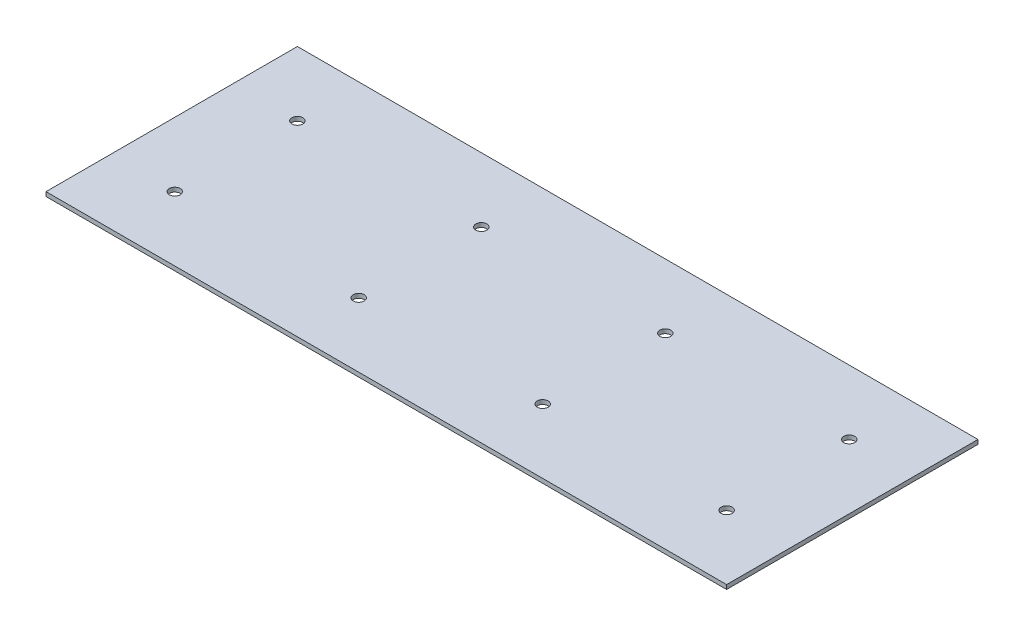
SolidWorks part; units mm, degrees
ref_plane "Front Plane" through (0, 0, 0) normal (0, 0, 1) x (1, 0, 0)
ref_plane "Top Plane" through (0, 0, 0) normal (0, 1, 0) x (1, 0, 0)
ref_plane "Right Plane" through (0, 0, 0) normal (1, 0, 0) x (0, 0, -1)
sketch "Sketch1" plane through (0, 0, 0) normal (0, 1, 0) x (1, 0, 0)
  line L1 (0, 0) -> (255.3, 0)
  line L2 (0, 0) -> (0, 94.3)
  line L3 (0, 94.3) -> (255.3, 94.3)
  line L4 (255.3, 0) -> (255.3, 94.3)
  dimension "D1" = 255.3
  dimension "D2" = 94.3
extrude "Boss-Extrude1" add sketch "Sketch1" along normal blind 1.6
ref_plane "Plane1" through (0, 0, -47.15) normal (0, 0, 1) x (1, 0, 0)
ref_plane "Plane2" through (127.65, 0, 0) normal (1, 0, 0) x (0, 0, -1)
sketch "Sketch3" plane through (0, 1.6, 0) normal (0, 1, 0) x (1, 0, 0)
  circle A0 centre (24.15, 70.15) radius 2.05
  circle A1 centre (24.15, 24.15) radius 2.05
  circle A3 centre (93.15, 70.15) radius 2.05
  circle A4 centre (93.15, 24.15) radius 2.05
  circle A5 centre (162.15, 24.15) radius 2.05
  circle A6 centre (162.15, 70.15) radius 2.05
  circle A8 centre (231.15, 70.15) radius 2.05
  circle A9 centre (231.15, 24.15) radius 2.05
  circle A11 centre (24.15, 70.15) radius 2.97 construction
  circle A12 centre (24.15, 24.15) radius 2.64 construction
  circle A13 centre (93.15, 70.15) radius 2.64 construction
  circle A14 centre (93.15, 24.15) radius 2.64 construction
  circle A15 centre (162.15, 70.15) radius 2.64 construction
  circle A16 centre (162.15, 24.15) radius 2.64 construction
  circle A17 centre (231.15, 70.15) radius 2.64 construction
  circle A18 centre (231.15, 24.15) radius 2.64 construction
  point P18 (0, 0)
  point P19 (23, 66)
  dimension "D1" = 4.1
extrude "Cut-Extrude1" cut sketch "Sketch3" against normal through all
